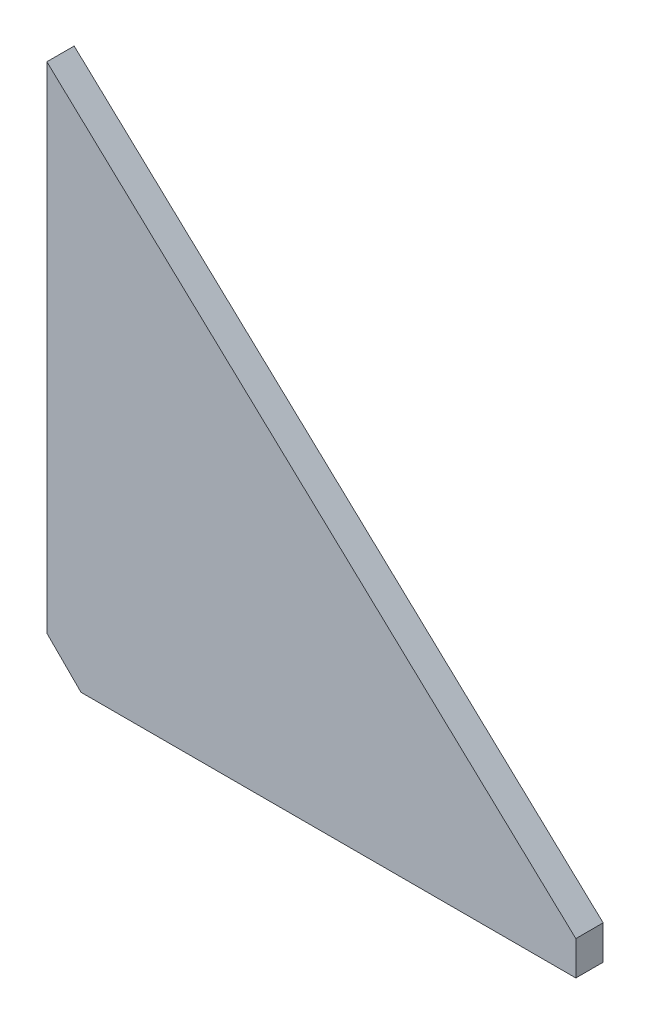
SolidWorks part; units mm, degrees
material "ASTM A36 Steel"
ref_plane "Front Plane" through (0, 0, 0) normal (0, 0, 1) x (1, 0, 0)
ref_plane "Top Plane" through (0, 0, 0) normal (0, 1, 0) x (1, 0, 0)
ref_plane "Right Plane" through (0, 0, 0) normal (1, 0, 0) x (0, 0, -1)
sketch "Sketch1" plane through (0, 0, 0) normal (0, 0, 1) x (1, 0, 0)
  line L0 (66.9214, -2.9896) -> (-78.0786, -2.9896)
  line L1 (-88.0786, 7.0104) -> (-88.0786, 152.0104)
  line L2 (-88.0786, 7.0104) -> (-78.0786, -2.9896)
  line L3 (66.9214, -2.9896) -> (66.9214, 7.0104)
  line L4 (66.9214, 7.0104) -> (-88.0786, 152.0104)
  dimension "D3" = 10
extrude "Boss-Extrude1" add sketch "Sketch1" along normal blind 8
